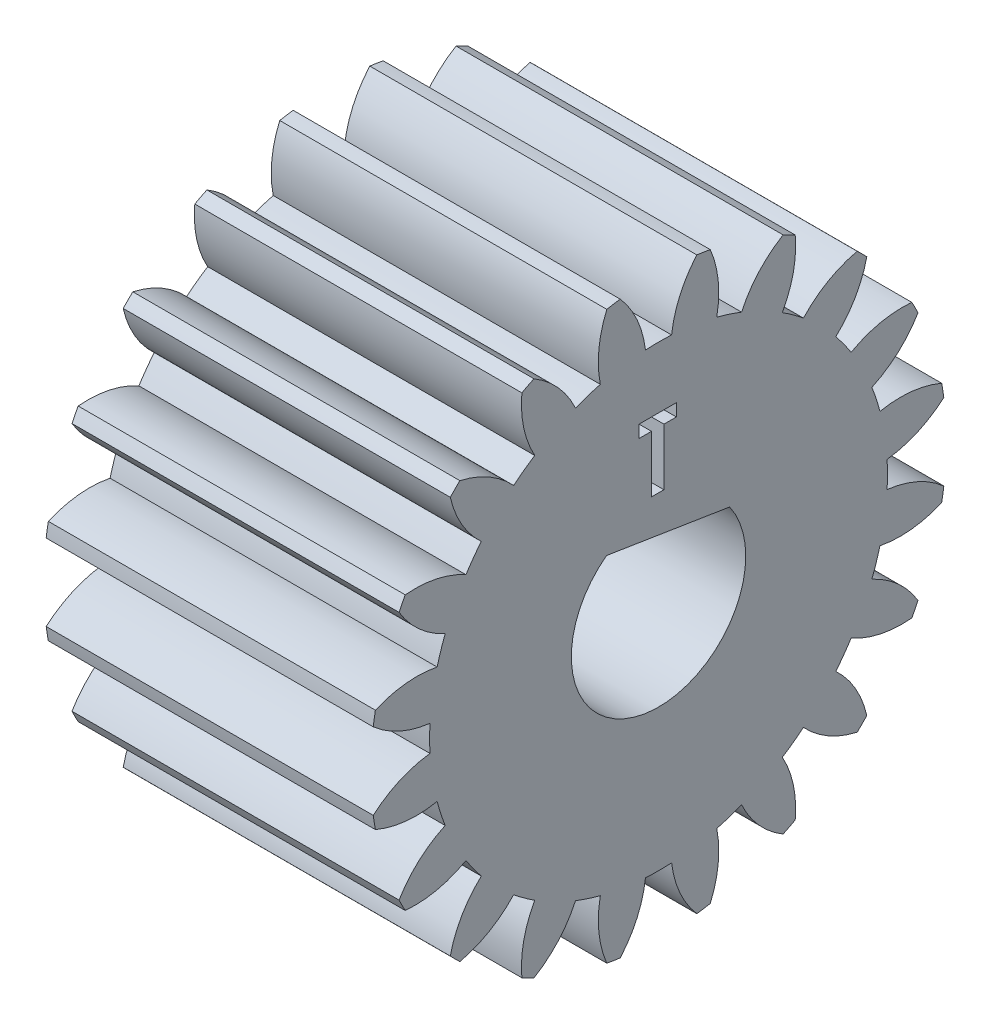
SolidWorks part; units mm, degrees
ref_plane "Plane1" through (0, 0, 0) normal (0, 0, 1) x (1, 0, 0)
ref_plane "Plane2" through (0, 0, 0) normal (0, 1, 0) x (1, 0, 0)
ref_plane "Plane3" through (0, 0, 0) normal (1, 0, 0) x (0, 0, -1)
sketch "HoldingSke" plane through (0, 0, 0) normal (0, 1, 0) x (1, 0, 0)
  line L0 (0, 0) -> (0.7831, -0.285)
  line L1 (-15, 0) -> (100, 0) construction
  line L2 (0, 0) -> (-2.1039, 2.3779)
  line L3 (0, 0) -> (-11.863, 4.5341)
  line L4 (0, 0) -> (8.1152, 2.9537)
  line L5 (0, 0) -> (-46.8476, -17.4728)
  line L6 (0, 0) -> (-12.4344, -8.3896)
  line L7 (-2.1039, 2.3779) -> (8.6586, 51.2059)
  line L8 (-76.2, 54.61) -> (-74.8, 54.61)
  line L9 (-71.009, 38.7566) -> (-53.1078, 45.2721)
  line L10 (-76.2, 71.12) -> (104.1128, 71.12)
  line L11 (0, 0) -> (-15, 0)
  line L12 (-76.2, 101.6) -> (-76.155, 101.6)
  line L13 (24.9733, 27.94) -> (52.9518, 28.4284)
  line L14 (24.9733, 27.94) -> (24.9743, 27.94)
  line L15 (24.9733, 27.94) -> (100.4006, 29.5858)
  line L16 (-63.627, -1.2) -> (-12.827, -1.2)
  circle A0 centre (0, 0) radius 4
  circle A1 centre (0, 0) radius 10.499
  circle A2 centre (0, 0) radius 37.5
  circle A3 centre (0, 0) radius 4
  dimension "MHD" = 20.998
  dimension "Hub_dia" = 75
  dimension "Bore" = 8
  dimension "MBD" = 8
  dimension "Num_teeth" = 20
  dimension "Pitch" = 0.8333
  dimension "Overall_len" = 50
  dimension "Show_teeth" = 20
  dimension "Thickness" = 15
  dimension "OAL" = 50.0001
  dimension "T_dim" = 1.4
  dimension "Ap" = 20
  dimension "H" = 19.05
  dimension "Pitch_radius" = 180.3128
  dimension "Width" = 15
  dimension "Backlash" = 0.045
  dimension "Addendum_fac" = 1
  dimension "Dedendum_fac" = 1.25
  dimension "Clearance_fac" = 0.25
  dimension "Dedendum_add" = 0.001
  dimension "Module" = 1.2
sketch "BasProSke" plane through (0, 0, 0) normal (0, 1, 0) x (1, 0, 0)
  line L0 (-10, 0) -> (60, 0) construction
  line L1 (0, 0) -> (0, 13.2)
  line L2 (0, 0) -> (15, 0)
  line L3 (15, 0) -> (15, 13.2)
  line L4 (15, 13.2) -> (0, 13.2)
  dimension "Thickness" = 15
  dimension "Diameter" = 26.4
revolve "Base-Revolve" add sketch "BasProSke" angle 360 about L0
sketch "TooCutSke" plane through (0, 0, 0) normal (1, 0, 0) x (0, 0, -1)
  line L1 (0, 0) -> (0, 107) construction
  line L2 (0, 0) -> (-1.0202, 11.9566) construction
  line L3 (0, 0) -> (-3.7447, 23.6432) construction
  line L4 (-1.0202, 11.9566) -> (-1.8724, 11.8216) construction
  arc A0 (0.599, 10.4819) -> (-0.599, 10.4819) centre (0, 0) ccw
  arc A1 (1.777, 13.1055) -> (-1.777, 13.1055) centre (0, 0) ccw
  circle A2 centre (0, 0) radius 12 construction
  circle A3 centre (0, 0) radius 11.2763 construction
  arc A4 (-0.599, 10.4819) -> (-1.777, 13.1055) centre (-5.3658, 9.9179) ccw
  arc A5 (1.777, 13.1055) -> (0.599, 10.4819) centre (5.3658, 9.9179) ccw
  dimension "Root_dia" = 20.998
  dimension "Overcut_dia" = 26.4508
  dimension "Pitch_dia" = 24
  dimension "Base_dia" = 22.5526
  dimension "Flank_rad" = 4.8
  dimension "Half_ang" = 9
  dimension "Half_CT" = 0.8628
extrude "ToothCut" cut sketch "TooCutSke" along normal through all
fillet "Breaks" [suppressed] radius 0.024
fillet "RootFillets" [suppressed] radius 0.301
pattern_circular "TeethCuts" count 20 every 18 about axis through (-10, 0, 0) along (1, 0, 0) of "ToothCut", "RootFillets", "Breaks"
sketch "HubNeaOneSke" plane through (0, 0, 0) normal (-1, 0, 0) x (0, 0, 1)
  circle A0 centre (0, 0) radius 10.499
  dimension "Diameter" = 20.998
extrude "HubNearOne" [suppressed] add sketch "HubNeaOneSke" along normal blind 35.0001
sketch "HubNeaBotSke" plane through (0, 0, 0) normal (-1, 0, 0) x (0, 0, 1)
  circle A0 centre (0, 0) radius 10.499
  dimension "Diameter" = 20.998
extrude "HubNearBoth" [suppressed] add sketch "HubNeaBotSke" along normal blind 17.5
ref_plane "FarPln" through (15, 0, 0) normal (1, 0, 0) x (0, 0, -1)
sketch "HubFarSke" plane through (15, 0, 0) normal (1, 0, 0) x (0, 0, -1)
  circle A0 centre (0, 0) radius 10.499
  dimension "Diameter" = 20.998
extrude "HubFar" [suppressed] add sketch "HubFarSke" along normal blind 17.5
sketch "BorSke" plane through (0, 0, 0) normal (1, 0, 0) x (0, 0, -1)
  circle A0 centre (0, 0) radius 4
  dimension "Diameter" = 8
extrude "Bore" cut sketch "BorSke" along normal mid plane 100.0001
sketch "KeySke" plane through (0, 0, 0) normal (1, 0, 0) x (0, 0, -1)
  line L0 (-1.5, 0) -> (-1.5, 5.4)
  line L1 (-1.5, 5.4) -> (1.5, 5.4)
  line L2 (1.5, 5.4) -> (1.5, 0)
  line L3 (0, 0) -> (0, 34) construction
  line L4 (-1.5, 0) -> (1.5, 0)
  dimension "Offset" = 5.4
  dimension "Width" = 3
extrude "Keyway" [suppressed] cut sketch "KeySke" along normal mid plane 100.0001
pattern_circular "Keyway2" [suppressed] count 2 every 90 about axis through (-10, 0, 0) along (1, 0, 0)
sketch "Sketch1" plane through (0, 0, 0) normal (-1, 0, 0) x (0, 0, 1)
  line L0 (0, 0) -> (0, 8) construction
  line L1 (0, 0) -> (-0.438, 2.7655) construction
  line L2 (-0.438, 2.7655) -> (-0.6257, 3.9508) construction
  line L3 (2.3834, 3.2124) -> (-3.2594, 2.3187)
  circle A0 centre (0, 0) radius 4 construction
  circle A1 centre (0, 0) radius 8 construction
  circle A2 centre (0, 0) radius 4 construction
  arc A3 (2.3834, 3.2124) -> (-3.2594, 2.3187) centre (0, 0) ccw
  point P12 (-0.438, 2.7655)
  dimension "D1" = 16
  dimension "D2" = 1.2
  dimension "D3" = 9
extrude "Boss-Extrude1" add sketch "Sketch1" against normal up to surface (15 mm away) up to face at (15, 0, 4)
sketch "Sketch2" plane through (0, 0, 0) normal (-1, 0, 0) x (0, 0, 1)
  circle A0 centre (0, 0) radius 6
  circle A1 centre (0, 0) radius 7.2
  dimension "D1" = 12
  dimension "D2" = 14.4
extrude "Cut-Extrude1" cut sketch "Sketch2" against normal blind 0.5
sketch "Sketch3" plane through (15, 0, 0) normal (1, 0, 0) x (0, 0, -1)
  text T0 "T" font "Century Gothic" height in points 12
extrude "Cut-Extrude2" cut sketch "Sketch3" against normal blind 2
equation "' \"Module@HoldingSke\" = 6.35"
equation "' \"Num_teeth@HoldingSke\" = 12"
equation "' \"Ap@HoldingSke\" =  20"
equation "' \"Ap@HoldingSke\" = 20"
equation "' \"Width@HoldingSke\" = 0.5 * 25.4"
equation "' \"Hub_dia@HoldingSke\"= 1 * 25.4"
equation "' \"Hub_dia@HoldingSke\" = 1 * 25.4"
equation "' \"Overall_len@HoldingSke\" = 1.0 * 25.4"
equation "' \"Bore@HoldingSke\" = 0.75 * 25.4"
equation "' \"T_dim@HoldingSke\" = 0.1 * 25.4"
equation "' \"Width@KeySke\" = 0.25 * 25.4"
equation "' \"Show_teeth@HoldingSke\" = 13"
equation "' \"Backlash@HoldingSke\" = 0.009 * 25.4"
equation "' \"Addendum_fac@HoldingSke\" = 1.0"
equation "' \"Dedendum_fac@HoldingSke\" = 1.25"
equation "' \"Dedendum_add@HoldingSke\" = 0.00005 * 25.4"
equation "' \"Clearance_fac@HoldingSke\" = 0.25"
equation "\"Pitch@HoldingSke\" = 1 / \"Module@HoldingSke\""
equation "\"Overcut_dia@TooCutSke\" = (\"Num_teeth@HoldingSke\" + 2 * \"Addendum_fac@HoldingSke\") / \"Pitch@HoldingSke\" + 0.002 * 25.4"
equation "\"Pitch_dia@TooCutSke\" = \"Num_teeth@HoldingSke\" / \"Pitch@HoldingSke\""
equation "\"Base_dia@TooCutSke\" = \"Num_teeth@HoldingSke\" / \"Pitch@HoldingSke\" * cos((\"Ap@HoldingSke\"  * 3.14159265 / 180))"
equation "\"Root_dia@TooCutSke\" = (\"Num_teeth@HoldingSke\" + 2) / \"Pitch@HoldingSke\" - 2 * (\"Addendum_fac@HoldingSke\" + \"Dedendum_fac@HoldingSke\") / \"Pitch@HoldingSke\" - \"Dedendum_add@HoldingSke\" * 2"
equation "\"Half_ang@TooCutSke\" = 180 / \"Num_teeth@HoldingSke\""
equation "\"Half_CT@TooCutSke\" = \"Num_teeth@HoldingSke\" / \"Pitch@HoldingSke\" * sin((3.14159265 / 2 / \"Num_teeth@HoldingSke\")) / 2 - 7 * \"Backlash@HoldingSke\" / 4"
equation "\"Flank_rad@TooCutSke\" = \"Num_teeth@HoldingSke\" / \"Pitch@HoldingSke\" / 5"
equation "\"Radius@RootFillets\" = \"Clearance_fac@HoldingSke\" / \"Pitch@HoldingSke\" + \"Dedendum_add@HoldingSke\""
equation "\"Break_rad@Breaks\" = 0.02 / \"Pitch@HoldingSke\""
equation "\"Thickness@HoldingSke\" = \"Width@HoldingSke\""
equation "\"OAL@HoldingSke\" = \"Thickness@HoldingSke\""
equation "\"MHD@HoldingSke\" = (\"Num_teeth@HoldingSke\" + 2) / \"Pitch@HoldingSke\" - 2 * (\"Addendum_fac@HoldingSke\" + \"Dedendum_fac@HoldingSke\")  / \"Pitch@HoldingSke\" - \"Dedendum_add@HoldingSke\" * 2"
equation "\"MBD@HoldingSke\" = (\"Num_teeth@HoldingSke\" + 2) / \"Pitch@HoldingSke\" - 2 * (\"Addendum_fac@HoldingSke\" + \"Dedendum_fac@HoldingSke\")  / \"Pitch@HoldingSke\" - \"Dedendum_add@HoldingSke\" * 2 - 0.002 * 25.4"
equation "\"MHD@HoldingSke\" = ((sgn( \"MHD@HoldingSke\" - \"Hub_dia@HoldingSke\" )-1)*( \"MHD@HoldingSke\" - \"Hub_dia@HoldingSke\" ))/-2+ \"Hub_dia@HoldingSke\""
equation "\"MBD@HoldingSke\" = ((sgn( \"MBD@HoldingSke\" - \"Bore@HoldingSke\" )-1)*( \"MBD@HoldingSke\" - \"Bore@HoldingSke\" ))/-2+ \"Bore@HoldingSke\""
equation "\"OAL@HoldingSke\" = ((sgn( \"OAL@HoldingSke\" - \"Overall_len@HoldingSke\" )+1)*( \"OAL@HoldingSke\" - \"Overall_len@HoldingSke\" ))/2 + \"Overall_len@HoldingSke\" + 0.000002 * 25.4"
equation "\"Num_teeth@TeethCuts\" = int( \"Show_teeth@HoldingSke\" ) + 1"
equation "\"Num_teeth@TeethCuts\" = ((sgn( \"Num_teeth@TeethCuts\" - \"Num_teeth@HoldingSke\" )-1)*( \"Num_teeth@TeethCuts\" - \"Num_teeth@HoldingSke\" ))/-2+ \"Num_teeth@HoldingSke\""
equation "\"Num_teeth@TeethCuts\" = ((sgn( \"Num_teeth@TeethCuts\" - 2.0)+1)*( \"Num_teeth@TeethCuts\" - 2.0))/2 +2.0"
equation "\"Angle@TeethCuts\" = 360.0 / \"Num_teeth@HoldingSke\""
equation "\"Diameter@BasProSke\" = (\"Num_teeth@HoldingSke\" + 2 * \"Addendum_fac@HoldingSke\") / \"Pitch@HoldingSke\""
equation "\"Thickness@BasProSke\"  = \"Thickness@HoldingSke\""
equation "' \"Fillet_rad@BasProSke\" =  \"Thickness@HoldingSke\" * 0.05"
equation "' \"Fillet_rad@BasProSke\" = \"Thickness@HoldingSke\" * 0.05"
equation "\"MHD@HoldingSke\" = ((sgn( \"MHD@HoldingSke\" - \"Root_dia@TooCutSke\" )-1)*( \"MHD@HoldingSke\" - \"Root_dia@TooCutSke\" ))/-2+ \"Root_dia@TooCutSke\""
equation "\"Diameter@HubNeaOneSke\" = \"MHD@HoldingSke\""
equation "\"Length@HubNearOne\" = \"OAL@HoldingSke\" - \"Thickness@BasProSke\""
equation "\"Diameter@HubNeaBotSke\" = \"MHD@HoldingSke\""
equation "\"Length@HubNearBoth\" = ( \"OAL@HoldingSke\" - \"Thickness@BasProSke\" ) / 2.0"
equation "\"Thickness@FarPln\" = \"Thickness@BasProSke\""
equation "\"Diameter@HubFarSke\" = \"MHD@HoldingSke\""
equation "\"Length@HubFar\" = ( \"OAL@HoldingSke\" - \"Thickness@BasProSke\" ) / 2.0"
equation "\"Diameter@BorSke\" = \"MBD@HoldingSke\""
equation "\"D1@Bore\" = \"OAL@HoldingSke\" * 2.0"
equation "\"D1@Keyway\" = \"OAL@HoldingSke\" * 2.0"
equation "\"Offset@KeySke\" = \"T_dim@HoldingSke\" + \"MBD@HoldingSke\" / 2.0"
